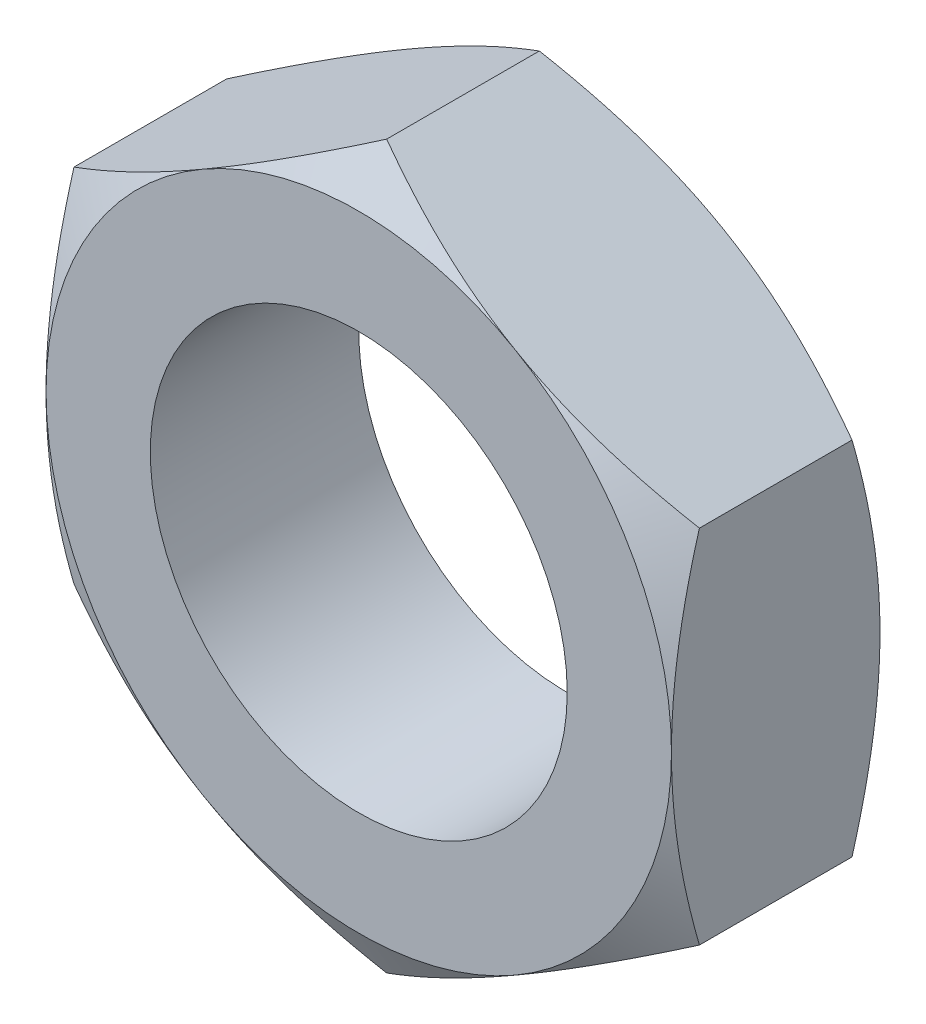
SolidWorks part; units mm, degrees
material "1.4000 (X6Cr13)"
ref_plane "Płaszczyzna przednia" through (0, 0, 0) normal (0, 0, 1) x (1, 0, 0)
ref_plane "Płaszczyzna górna" through (0, 0, 0) normal (0, 1, 0) x (1, 0, 0)
ref_plane "Płaszczyzna prawa" through (0, 0, 0) normal (1, 0, 0) x (0, 0, -1)
sketch "Szkic1" plane through (0, 0, 0) normal (0, 0, 1) x (1, 0, 0)
  line L1 (-13.5, 7.7942) -> (-13.5, -7.7942)
  line L2 (-13.5, -7.7942) -> (0, -15.5885)
  line L3 (0, -15.5885) -> (13.5, -7.7942)
  line L4 (13.5, -7.7942) -> (13.5, 7.7942)
  line L5 (13.5, 7.7942) -> (0, 15.5885)
  line L6 (0, 15.5885) -> (-13.5, 7.7942)
  circle A0 centre (0, 0) radius 9
  circle A1 centre (0, 0) radius 13.5 construction
  dimension "d" = 18
  dimension "s" = 27
extrude "Dodanie-wyciągnięcie1" add sketch "Szkic1" along normal mid plane 9
sketch "Szkic2" plane through (0, 0, 4.5) normal (0, 0, 1) x (1, 0, 0)
  circle A0 centre (0, 0) radius 13.5
  dimension "D1" = 27
extrude "Wytnij-wyciągnięcie2" cut sketch "Szkic2" against normal blind 9 draft 60 flip side to cut
mirror "Lustro1" about plane through (0, 0, 0) normal (0, 0, 1) of "Wytnij-wyciągnięcie2"
equation "\"D1@Szkic2\" = \"s@Szkic1\""
equation "\"D1@Wytnij-wyciągnięcie2\" = \"m@Dodanie-wyciągnięcie1\""
